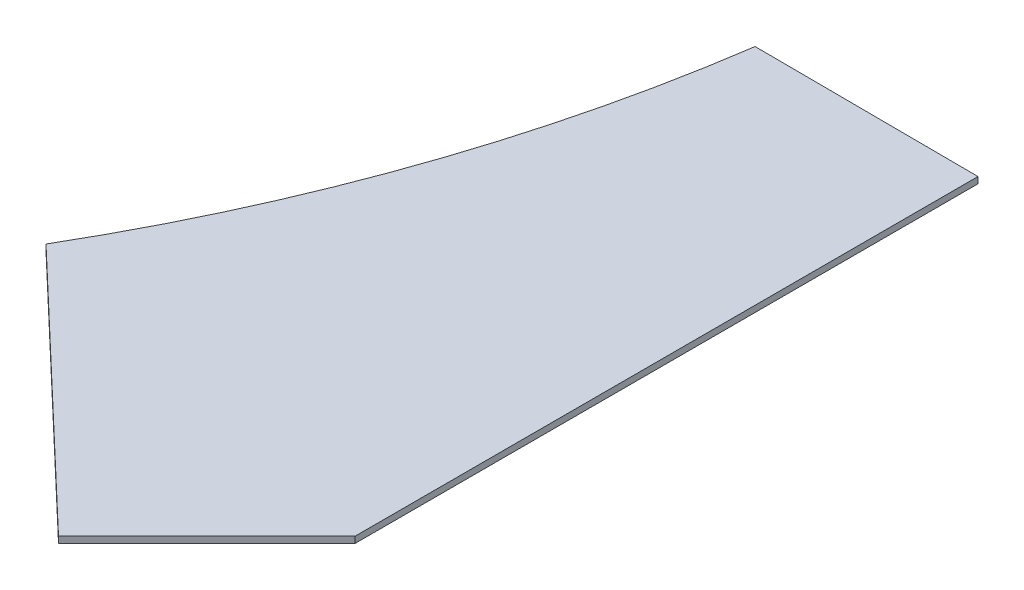
SolidWorks part; units mm, degrees
ref_plane "Front Plane" through (0, 0, 0) normal (0, 0, 1) x (1, 0, 0)
ref_plane "Top Plane" through (0, 0, 0) normal (0, 1, 0) x (1, 0, 0)
ref_plane "Right Plane" through (0, 0, 0) normal (1, 0, 0) x (0, 0, -1)
sketch "Sketch1" plane through (0, 0, 0) normal (0, 1, 0) x (1, 0, 0)
  line L7 (264, 0) -> (264, 131.98)
  line L9 (131.9796, 264) -> (0, 264)
  line L14 (131.9796, 264) -> (264, 131.98)
  line L15 (0, 264) -> (0, 0) construction
  line L16 (264, 109.3524) -> (186.6762, 186.6762) [skipped]
  line L17 (0, 0) -> (264, 0) construction
  line L18 (264, -131.9796) -> (131.98, -264)
  line L19 (-264, 0) -> (-264, -109.3524) [skipped]
  line L20 (-186.6762, 186.6762) -> (-264, 109.3524) [skipped]
  line L21 (-186.6762, -186.6762) -> (-109.3524, -264) [skipped]
  line L22 (0, -264) -> (109.3524, -264) [skipped]
  line L23 (186.6762, -186.6762) -> (264, -109.3524) [skipped]
  line L24 (264, -131.9796) -> (264, 0)
  line L25 (0, -264) -> (131.98, -264)
  line L26 (-131.9796, -264) -> (-264, -131.98)
  line L27 (-131.9796, -264) -> (0, -264)
  line L28 (-264, 0) -> (-264, -131.98)
  line L29 (-264, 131.9796) -> (-131.98, 264)
  line L30 (-264, 131.9796) -> (-264, 0)
  line L31 (0, 264) -> (-131.98, 264)
  arc A0 (264, 0) -> (0, 264) centre (0, 0) ccw construction
  point P33 (0, 0)
  dimension "D1" = 264
  dimension "D2" = 280
  dimension "D3" = 131.98
  dimension "D4" = 4
extrude "baseplate profile" add sketch "Sketch1" against normal blind 2
sketch "Sketch2" plane through (0, 0, 0) normal (0, 1, 0) x (1, 0, 0)
  line L0 (0, -248) -> (0, 248) construction
  circle A0 centre (0, 248) radius 1
  dimension "D2" = 2
  dimension "D1" = 496
extrude "M3 pins" add sketch "Sketch2" along normal blind 5 draft 7
sketch "center line" plane through (0, 0, 0) normal (0, 0, 1) x (1, 0, 0)
  line L0 (0, 0) -> (0, 200) construction
  dimension "D1" = 200
pattern_circular "CirPattern1" count 32 over 360 about axis through (0, 0, 0) along (0, 1, 0) of "M3 pins"
sketch "Sketch4" plane through (0, 0, 0) normal (0, 1, 0) x (1, 0, 0)
  line L0 (0, 0) -> (0, 201) construction
  line L1 (-9, 201) -> (9, 201) construction
  circle A0 centre (9, 201) radius 1
  circle A1 centre (-9, 201) radius 1
  point P5 (0, 201)
  dimension "D3" = 2
  dimension "D4" = 2
  dimension "D1" = 201
  dimension "D2" = 18
extrude "pillar pins" add sketch "Sketch4" along normal blind 5 draft 6
pattern_circular "CirPattern2" count 6 over 360 about axis through (0, 0, 0) along (0, 1, 0) of "pillar pins"
sketch "Sketch5" plane through (0, 0, 0) normal (0, 1, 0) x (1, 0, 0)
  line L0 (-193.0402, 193.0402) -> (193.0402, -193.0402) construction
  line L1 (-131.9796, -264) -> (131.98, -264) construction
  circle A0 centre (-193.0402, 193.0402) radius 3
  dimension "D3" = 6
  dimension "D1" = 546
  dimension "D2" = 45
extrude "M8 hole -1" add sketch "Sketch5" along normal blind 5 draft 12
pattern_circular "M8 -1 pattern" count 4 over 360 about axis through (0, 0, 0) along (0, 1, 0) of "M8 hole -1"
sketch "Sketch6" plane through (0, 0, 0) normal (0, 1, 0) x (1, 0, 0)
  line L0 (0, 0) -> (0, -324.5462) construction
  line L1 (0, 0) -> (-438.1399, 0) construction
  circle A0 centre (-125, -250) radius 3
  dimension "D1" = 6
  dimension "D2" = 125
  dimension "D3" = 250
extrude "M8 -2" add sketch "Sketch6" along normal blind 5 draft 12
pattern_circular "M8 -2 pattern" count 4 over 360 about axis through (0, 0, 0) along (0, 1, 0) of "M8 -2"
pattern_circular "M8 -3" count 2 over 36.9 about axis through (0, 0, 0) along (0, 1, 0) of "M8 -2 pattern", "M8 -2"
sketch "Sketch7" [suppressed] plane through (0, 0, 0) normal (0, 1, 0) x (1, 0, 0)
  line L1 (94.9211, 86.9806) -> (274.9211, 86.9806)
  line L2 (94.9211, 86.9806) -> (94.9211, -93.0194)
  line L3 (94.9211, -93.0194) -> (274.9211, -93.0194)
  line L4 (274.9211, 86.9806) -> (274.9211, -93.0194)
  dimension "D1" = 180
  dimension "D2" = 180
sketch "Sketch8" plane through (0, 0, 0) normal (0, 1, 0) x (1, 0, 0)
  line L0 (0, 0) -> (0, -180) construction
  line L1 (20, -230) -> (-20, -230)
  line L2 (20, -230) -> (20, -180)
  line L3 (20, -180) -> (-20, -180)
  line L4 (-20, -230) -> (-20, -180)
  line L5 (0, 0) -> (115.434, -199.9375)
  line L6 (0, 0) -> (-115.434, -199.9375)
  arc A0 (20, -230) -> (115.434, -199.9375) centre (0, 0) ccw
  arc A1 (-20, -230) -> (-115.434, -199.9375) centre (0, 0) cw
  point P7 (0, -180)
  dimension "D4" = 30
  dimension "D1" = 40
  dimension "D2" = 180
  dimension "D3" = 50
extrude "cut center" cut sketch "Sketch8" against normal through all contours L5 L0 L3 L2 A0 | L0 L6 A1 L4 L3
pattern_circular "CirPattern7" count 6 over 360 about axis through (0, 0, 0) along (0, 1, 0) of "cut center"
sketch "middle piece space " plane through (0, 0, 0) normal (0, 1, 0) x (1, 0, 0)
  line L0 (0, 0) -> (-200, 0) construction
  line L1 (91, 110) -> (-91, 110)
  line L2 (-110, 91) -> (-290, 91)
  line L3 (-110, 91) -> (-110, -91)
  line L4 (-110, -91) -> (-290, -91)
  line L5 (-290, 91) -> (-290, -91)
  line L6 (-110, 91) -> (-290, -91) construction
  line L7 (-110, -91) -> (-290, 91) construction
  line L8 (91, 110) -> (91, 290)
  line L9 (91, 290) -> (-91, 290)
  line L10 (-91, 110) -> (-91, 290)
  line L11 (110, -91) -> (110, 91)
  line L12 (110, -91) -> (290, -91)
  line L13 (290, -91) -> (290, 91)
  line L14 (110, 91) -> (290, 91)
  line L15 (-91, -110) -> (91, -110)
  line L16 (-91, -110) -> (-91, -290)
  line L17 (-91, -290) -> (91, -290)
  line L18 (91, -110) -> (91, -290)
  point P22 (0, 0)
  dimension "D1" = 182
  dimension "D2" = 200
  dimension "D3" = 180
  dimension "D4" = 4
sketch "Sketch11" plane through (0, 0, 0) normal (0, 1, 0) x (1, 0, 0)
  line L0 (-131.9796, -264) -> (131.98, -264) construction
  line L1 (-91, -91) -> (-264, -91)
  line L2 (-91, -91) -> (-91, -264)
  line L3 (-91, -264) -> (-264, -264)
  line L4 (-264, -91) -> (-264, -264)
  line L5 (-264, 131.9796) -> (-264, -131.98) construction
  line L6 (-110, -91) -> (-290, -91) construction
  line L7 (-91, -110) -> (-91, -290) construction
sketch "Sketch13" plane through (0, -2, 0) normal (0, -1, 0) x (1, 0, 0)
  line L1 (295.8455, -414.0765) -> (-305.4926, -414.0765)
  line L2 (295.8455, -414.0765) -> (295.8455, 361.6153)
  line L3 (295.8455, 361.6153) -> (-305.4926, 361.6153)
  line L4 (-305.4926, -414.0765) -> (-305.4926, 361.6153)
  line L5 (-91, 91) -> (-264, 91)
  line L6 (-91, 91) -> (-91, 264)
  line L7 (-91, 264) -> (-264, 264)
  line L8 (-264, 91) -> (-264, 264)
extrude "Cut-Extrude2" [suppressed] cut sketch "Sketch13" against normal blind 10
sketch "Sketch14" plane through (0, 0, 0) normal (0, 1, 0) x (1, 0, 0)
  line L4 (-106, -244) -> (-83.5, -256.9904)
  line L5 (-83.5, -256.9904) -> (-83.5, -231.0096)
  line L6 (-83.5, -231.0096) -> (-106, -244)
  line L7 (-91, -264) -> (-264, -264) construction
  line L8 (-91, -110) -> (-91, -290) construction
  circle A0 centre (-91, -244) radius 7.5 construction
  dimension "D2" = 15
  dimension "D3" = 20
extrude "Boss-Extrude1" [suppressed] add sketch "Sketch14" against normal up to surface (2 mm away)
sketch "Sketch15" plane through (0, 0, 0) normal (0, 1, 0) x (1, 0, 0)
  line L0 (-110, -91) -> (-290, -91) construction
  line L1 (-256.9904, -98.5) -> (-231.0096, -98.5)
  line L2 (-231.0096, -98.5) -> (-244, -76)
  line L3 (-244, -76) -> (-256.9904, -98.5)
  line L4 (-264, -91) -> (-264, -264) construction
  circle A0 centre (-244, -91) radius 7.5 construction
  dimension "D1" = 15
  dimension "D2" = 20
extrude "Cut-Extrude3" [suppressed] cut sketch "Sketch15" against normal through all
sketch "Sketch16" plane through (0, -2, 0) normal (0, -1, 0) x (1, 0, 0)
  line L0 (110, 91) -> (290, 91) construction
  line L1 (91, 290) -> (290, 290)
  line L2 (91, 290) -> (91, 91)
  line L3 (91, 91) -> (290, 91)
  line L4 (290, 290) -> (290, 91)
  line L5 (91, 110) -> (91, 290) construction
  line L6 (-91, 290) -> (91, 290) construction
  line L7 (290, 91) -> (290, -91) construction
  line L9 (365.1131, -507.1986) -> (-340.9024, -507.1986)
  line L10 (365.1131, -507.1986) -> (365.1131, 455.048)
  line L11 (365.1131, 455.048) -> (-340.9024, 455.048)
  line L12 (-340.9024, -507.1986) -> (-340.9024, 455.048)
extrude "Cut-Extrude4" cut sketch "Sketch16" against normal through all
sketch "Sketch17" plane through (0, 0, 0) normal (0, 1, 0) x (1, 0, 0)
  line L0 (91, -264) -> (131.98, -264) construction
  line L1 (81, -244) -> (96, -252.6603)
  line L2 (96, -252.6603) -> (96, -235.3397)
  line L3 (96, -235.3397) -> (81, -244)
  line L4 (91, -110) -> (91, -290) construction
  circle A0 centre (91, -244) radius 5 construction
  dimension "D1" = 10
  dimension "D2" = 20
extrude "Cut-Extrude5" cut sketch "Sketch17" against normal through all
sketch "Sketch19" plane through (0, -2, 0) normal (0, -1, 0) x (-1, 0, 0)
  line L0 (-212.1768, -91) -> (-264, -91) construction
  line L1 (-235.3397, -86) -> (-252.6603, -86)
  line L2 (-252.6603, -86) -> (-244, -101)
  line L3 (-244, -101) -> (-235.3397, -86)
  line L4 (-264, -131.9796) -> (-264, -91) construction
  circle A0 centre (-244, -91) radius 5 construction
  dimension "D1" = 10
  dimension "D2" = 20
extrude "Boss-Extrude3" add sketch "Sketch19" against normal up to surface (2 mm away) contours L1 L2 L3 up to face at (155.3962, 0, 170.4232)
sketch "Sketch20" plane through (0, -2, 0) normal (0, -1, 0) x (1, 0, 0)
  line L0 (240.4949, 155.4847) -> (264, 131.9796)
  line L1 (264, 131.9796) -> (264, 33.2298)
  line L2 (264, 131.9796) -> (264, 0) construction
  line L3 (264, 131.9796) -> (131.98, 264) construction
  line L4 (240.4949, 155.4847) -> (199.3953, 116.368)
  line L5 (228.4896, 33.0531) -> (264, 33.2298)
  arc A0 (199.3953, 116.368) -> (228.4896, 33.0531) centre (0, 0) cw
  arc A1 (212.1768, 91) -> (209.1858, 97.6795) centre (0, 0) ccw construction
extrude "Boss-Extrude4" add sketch "Sketch20" along normal blind 1
sketch "Sketch21" plane through (0, -2, 0) normal (0, -1, 0) x (1, 0, 0)
  line L1 (365.7448, 322.5801) -> (39.3196, 322.5801)
  line L2 (365.7448, 322.5801) -> (365.7448, -41.9583)
  line L3 (365.7448, -41.9583) -> (39.3196, -41.9583)
  line L4 (39.3196, 322.5801) -> (39.3196, -41.9583)
extrude "Cut-Extrude6" cut sketch "Sketch21" against normal through all
